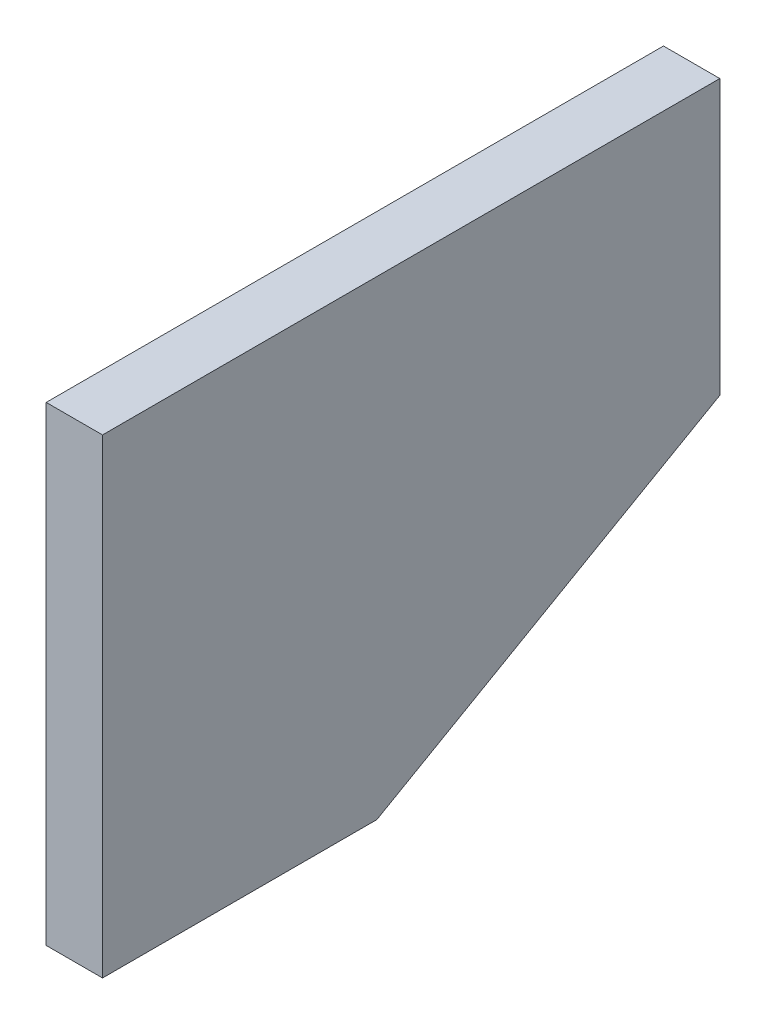
SolidWorks part; units mm, degrees
material "Pine"
ref_plane "Front Plane" through (0, 0, 0) normal (0, 0, 1) x (1, 0, 0)
ref_plane "Top Plane" through (0, 0, 0) normal (0, 1, 0) x (1, 0, 0)
ref_plane "Right Plane" through (0, 0, 0) normal (1, 0, 0) x (0, 0, -1)
sketch "Sketch1" plane through (0, 0, 0) normal (1, 0, 0) x (0, 0, -1)
  line L0 (0, 0) -> (200.025, 0)
  line L1 (200.025, 0) -> (200.025, -88.9)
  line L2 (200.025, -88.9) -> (88.9, -152.4)
  line L3 (88.9, -152.4) -> (0, -152.4)
  line L4 (0, -152.4) -> (0, 0)
  dimension "D1" = 88.9
  dimension "D2" = 88.9
  dimension "D3" = 200.025
  dimension "D4" = 152.4
extrude "Boss-Extrude1" add sketch "Sketch1" along normal blind 18.2562
equation "\"D3@Sketch1\"=4.375+3.5"
